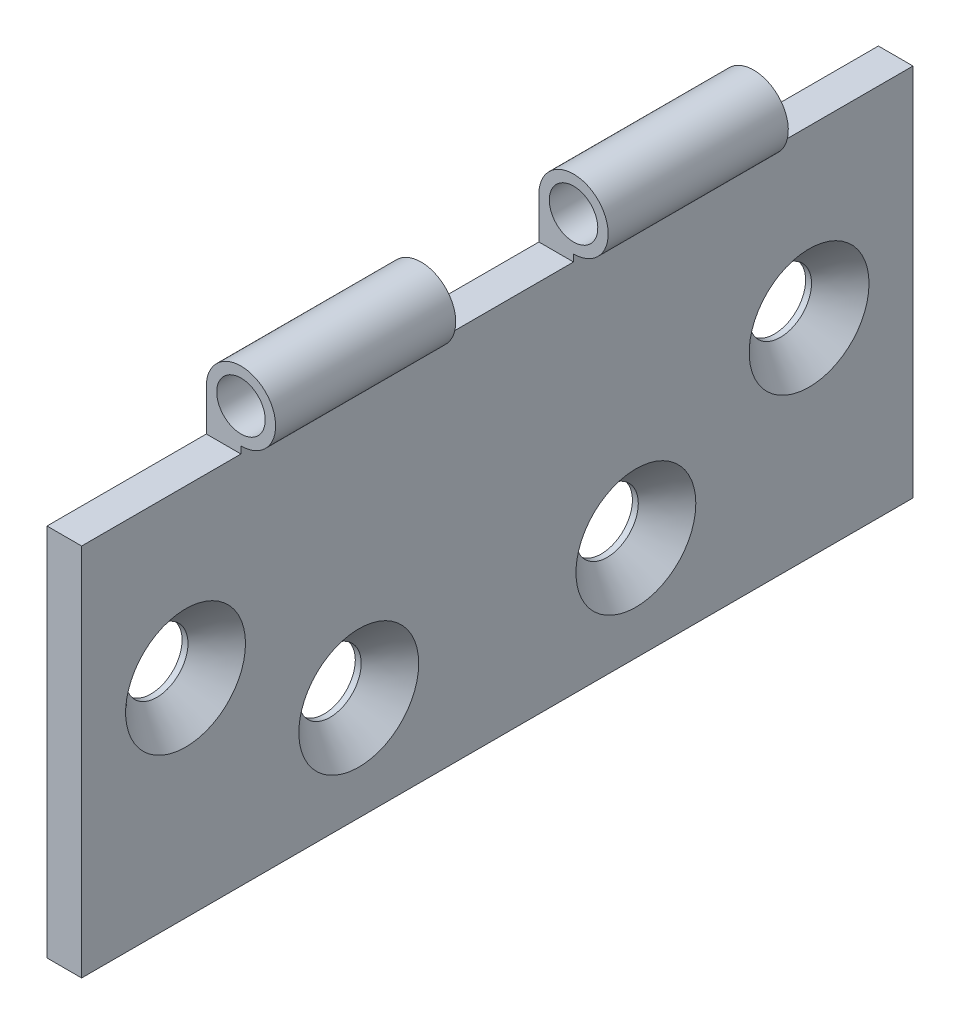
SolidWorks part; units mm, degrees
ref_plane "Front Plane" through (0, 0, 0) normal (0, 0, 1) x (1, 0, 0)
ref_plane "Top Plane" through (0, 0, 0) normal (0, 1, 0) x (1, 0, 0)
ref_plane "Right Plane" through (0, 0, 0) normal (1, 0, 0) x (0, 0, -1)
sketch "Эскиз1" plane through (0, 0, 0) normal (0, 0, 1) x (1, 0, 0)
  line L0 (0, 0) -> (0, 60)
  dimension "D1" = 60
extrude "Вытянуть-Тонкостенный1" add sketch "Эскиз1" along normal mid plane 120 thin
sketch "Эскиз2" plane through (0, 0, 60) normal (0, 0, 1) x (1, 0, 0)
  circle A0 centre (5, 60) radius 5
sweep "По траектории1" add profiles "Эскиз2" path edge at (5, 60, 0)
sketch "Эскиз4" plane through (0, 0, 60) normal (0, 0, 1) x (1, 0, 0)
  circle A0 centre (5, 60) radius 3.5
  arc A1 (5, 55) -> (0, 60) centre (5, 60) ccw construction
extrude "Вырез-Вытянуть1" cut sketch "Эскиз4" against normal through all
hole_wizard "Зенковка для  винта с плоской головкой M81" positions "Эскиз6" profile "Эскиз5" countersink size "M8" standard "Ansi Metric" end condition through all
sketch "Эскиз6" plane through (5, 0, 0) normal (1, 0, 0) x (0, 0, -1)
  point P0 (-45, 30)
  point P2 (-20, 15)
  dimension "D1" = 30
  dimension "D2" = 15
  dimension "D3" = 15
  dimension "D4" = 40
sketch "Эскиз5" plane through (5, 30, 45) normal (0, 1, 0) x (0, 0, -1)
  line L0 (0, 0) -> (0, 5)
  line L1 (0, 5) -> (4.5, 5)
  line L2 (4.5, 5) -> (4.5, 4.15)
  line L3 (4.5, 4.15) -> (8.65, 0)
  line L5 (8.65, 0) -> (0, 0)
  line L6 (-4.5, 4.15) -> (-8.65, 0) construction
  line L11 (0, -6.35) -> (0, 107.95) construction
  dimension "Диаметр сквозного отверстия" = 9
  dimension "Глубина сквозного отверстия" = 5
  dimension "Диаметр передней зенковки" = 17.3
  dimension "Угол передней зенковки" = 90
mirror "Зеркальное отражение1" about plane through (0, 0, 0) normal (0, 0, 1) of "Зенковка для  винта с плоской головкой M81"
sketch "компоновка для вырезов" plane through (5, 0, 0) normal (1, 0, 0) x (0, 0, -1)
  line L0 (-60, 65) -> (-60, 55) construction
  line L1 (60, 55) -> (60, 65) construction
  line L2 (-60, 65) -> (-60, 54)
  line L3 (60, 54) -> (-60, 54)
  line L4 (60, 54) -> (-60, 54)
  line L5 (60, 54) -> (60, 65)
  line L6 (-36, 65) -> (-36, 54)
  line L7 (60, 65) -> (-60, 65) construction
  line L8 (-12, 65) -> (-12, 54)
  line L9 (0, 81.1737) -> (0, 0) construction
  line L10 (12, 65) -> (12, 54)
  line L11 (36, 65) -> (36, 54)
  dimension "D2" = 24
  dimension "D3" = 24
  dimension "D1" = 1
sketch "Эскиз7" plane through (5, 0, 0) normal (1, 0, 0) x (0, 0, -1)
  line L0 (60, 54) -> (60, 65) construction
  line L1 (60, 54) -> (-60, 54) construction
  line L2 (-60, 65) -> (-60, 54) construction
  line L3 (60, 54) -> (60, 65)
  line L4 (60, 54) -> (37, 54)
  line L5 (-60, 65) -> (-60, 54)
  line L6 (60, 65) -> (37, 65)
  line L7 (-37, 65) -> (-60, 65)
  line L8 (-37, 54) -> (-60, 54)
  line L9 (-37, 65) -> (-37, 54)
  line L10 (-37, 65) -> (-37, 54)
  line L12 (-11, 65) -> (-11, 54)
  line L13 (-11, 65) -> (-11, 54)
  line L14 (11, 65) -> (-11, 65)
  line L15 (11, 65) -> (11, 54)
  line L16 (11, 65) -> (11, 54)
  line L18 (37, 65) -> (37, 54)
  line L19 (37, 65) -> (37, 54)
  line L20 (11, 54) -> (-11, 54)
  dimension "D2" = 1
  dimension "D3" = 1
  dimension "D4" = 1
  dimension "D5" = 1
extrude "Вырез-Вытянуть2" cut sketch "Эскиз7" against normal through all both and the other way through all
equation "\"D1@Эскиз6\"= \"D1@Эскиз1\" / 2"
equation "\"D4@Эскиз6\"= \"D1@Вытянуть-Тонкостенный1\" / 3"
equation "\"D2@компоновка для вырезов\"= \"D1@Вытянуть-Тонкостенный1\"/5"
equation "\"D3@компоновка для вырезов\"= \"D1@Вытянуть-Тонкостенный1\" / 5"
